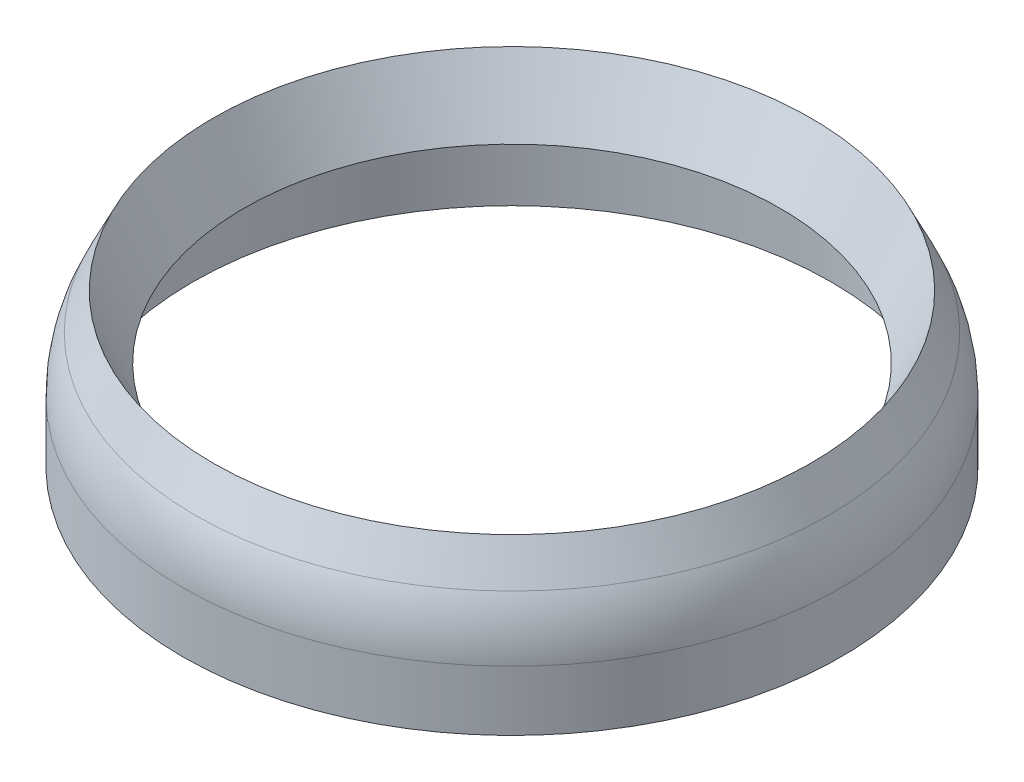
SolidWorks part; units mm, degrees
ref_plane "Front Plane" through (0, 0, 0) normal (0, 0, 1) x (1, 0, 0)
ref_plane "Top Plane" through (0, 0, 0) normal (0, 1, 0) x (1, 0, 0)
ref_plane "Right Plane" through (0, 0, 0) normal (1, 0, 0) x (0, 0, -1)
sketch "Sketch1" plane through (0, 0, 0) normal (0, 1, 0) x (1, 0, 0)
  circle A0 centre (0, 0) radius 25.8
  circle A1 centre (0, 0) radius 25
  dimension "D1" = 51.6
  dimension "D2" = 50
extrude "Boss-Extrude1" add sketch "Sketch1" against normal blind 7
sketch "Sketch2" plane through (0, 0, 0) normal (0, 1, 0) x (1, 0, 0)
  circle A0 centre (0, 0) radius 25.8
  circle A1 centre (0, 0) radius 21
  dimension "D1" = 42
  dimension "D2" = 51.6
extrude "Boss-Extrude2" add sketch "Sketch2" along normal blind 5 draft 26
fillet "Fillet3" radius 10 1 edges at (0, 0, 25.8)
